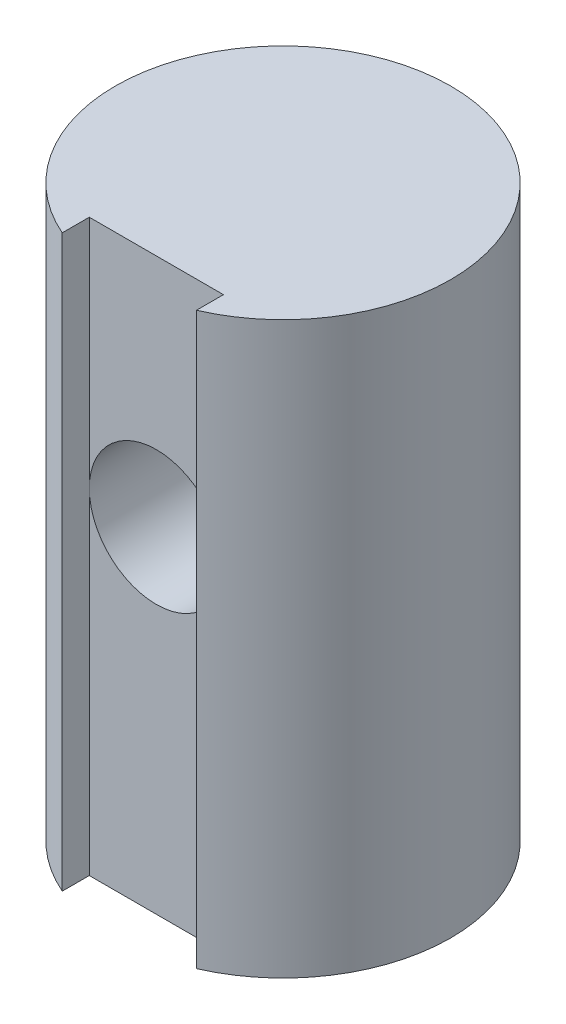
SolidWorks part; units mm, degrees
ref_plane "Front Plane" through (0, 0, 0) normal (0, 0, 1) x (1, 0, 0)
ref_plane "Top Plane" through (0, 0, 0) normal (0, 1, 0) x (1, 0, 0)
ref_plane "Right Plane" through (0, 0, 0) normal (1, 0, 0) x (0, 0, -1)
sketch "Sketch1" plane through (0, 0, 0) normal (0, 1, 0) x (1, 0, 0)
  circle A0 centre (0, 0) radius 15.875
  dimension "D1" = 31.75
extrude "cylinder" add sketch "Sketch1" along normal blind 53.975
sketch "Sketch2" plane through (0, 53.975, 0) normal (0, 1, 0) x (1, 0, 0)
  line L0 (0, -15.875) -> (0, -11.9888) construction
  line L1 (-6.35, -11.9888) -> (6.35, -11.9888)
  line L2 (-6.35, -11.9888) -> (-6.35, -24.6888)
  line L3 (-6.35, -24.6888) -> (6.35, -24.6888)
  line L4 (6.35, -11.9888) -> (6.35, -24.6888)
  line L5 (-6.35, -11.9888) -> (6.35, -24.6888) construction
  line L6 (-6.35, -24.6888) -> (6.35, -11.9888) construction
  line L7 (0, 0) -> (0, -11.9888) construction
  circle A0 centre (0, 0) radius 15.875 construction
  point P0 (0, -18.3388)
  dimension "D1" = 3.8862
  dimension "D2" = 12.7
  dimension "D3" = 12.7
extrude "flue track" cut sketch "Sketch2" against normal blind 76.2
sketch "Sketch3" plane through (0, 0, 0) normal (0, 0, 1) x (1, 0, 0)
  line L0 (6.35, 53.975) -> (-6.35, 53.975) construction
  line L1 (0, 53.975) -> (0, 31.75) construction
  circle A0 centre (0, 31.75) radius 6.35
  point P5 (0, 38.1)
  dimension "D1" = 12.7
  dimension "D2" = 15.875
extrude "air duct" cut sketch "Sketch3" against normal through all both and the other way through all
